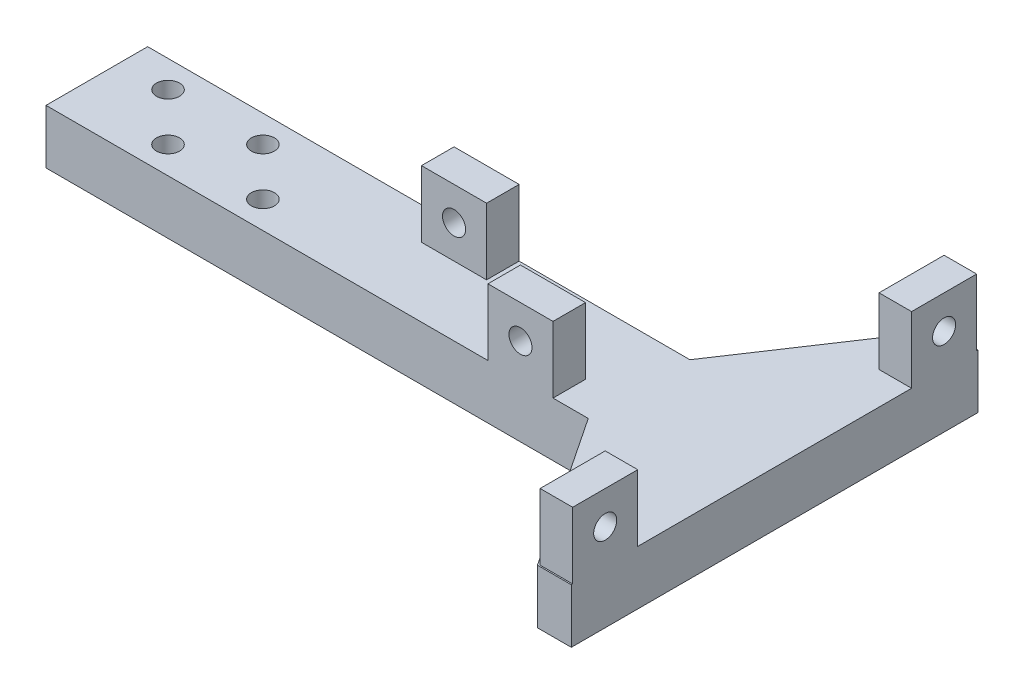
SolidWorks part; units mm, degrees
ref_plane "前视基准面" through (0, 0, 0) normal (0, 0, 1) x (1, 0, 0)
ref_plane "上视基准面" through (0, 0, 0) normal (0, 1, 0) x (1, 0, 0)
ref_plane "右视基准面" through (0, 0, 0) normal (1, 0, 0) x (0, 0, -1)
sketch "Sketch1" plane through (0, 0, 0) normal (0, 1, 0) x (1, 0, 0)
  line L0 (50, 30) -> (50, -30)
  line L1 (-50, 30) -> (50, 30) construction
  line L2 (-50, 30) -> (-50, -30) construction
  line L3 (-50, -30) -> (50, -30) construction
  line L4 (50, 30) -> (50, -30) construction
  line L5 (-50, 30) -> (50, -30) construction
  line L6 (-50, -30) -> (50, 30) construction
  line L7 (50, -30) -> (45, -30)
  line L8 (50, 30) -> (45, 30)
  line L9 (-50, 7.5) -> (-50, -7.5)
  line L10 (-50, 7.5) -> (30, 7.5)
  line L11 (30, 7.5) -> (30, -7.5) construction
  line L12 (30, -7.5) -> (-50, -7.5)
  line L13 (30, 7.5) -> (45, 30)
  line L14 (30, -7.5) -> (45, -30)
  point P0 (0, 0)
  point P5 (-50, 0)
  dimension "D1" = 15
  dimension "D2" = 20
  dimension "D3" = 5
  dimension "D4" = 60
  dimension "D5" = 100
extrude "Boss-Extrude1" add sketch "Sketch1" along normal blind 8
sketch "Sketch2" plane through (0, 8, 0) normal (0, 1, 0) x (1, 0, 0)
  line L0 (-50, 0) -> (50, 0) construction
  line L1 (50, 29.8) -> (45.2, 29.8)
  line L2 (50, 29.8) -> (50, 20.2)
  line L3 (50, 20.2) -> (45.2, 20.2)
  line L4 (45.2, 29.8) -> (45.2, 20.2)
  line L5 (-50, 7.5) -> (-50, -7.5) construction
  line L6 (50, -30) -> (50, 30) construction
  line L7 (45.2, -29.8) -> (45.2, -20.2)
  line L8 (50, -20.2) -> (45.2, -20.2)
  line L9 (50, -29.8) -> (50, -20.2)
  line L10 (50, -29.8) -> (45.2, -29.8)
  line L12 (24.8, -2.7) -> (15.2, -2.7)
  line L13 (24.8, -2.7) -> (24.8, -7.5)
  line L14 (24.8, -7.5) -> (15.2, -7.5)
  line L15 (15.2, -2.7) -> (15.2, -7.5)
  line L16 (-50, -7.5) -> (30, -7.5) construction
  line L17 (4.8, 2.7) -> (-4.8, 2.7)
  line L18 (4.8, 2.7) -> (4.8, 7.5)
  line L19 (4.8, 7.5) -> (-4.8, 7.5)
  line L20 (-4.8, 2.7) -> (-4.8, 7.5)
  line L21 (30, 7.5) -> (-50, 7.5) construction
  line L22 (50, 30) -> (45, 30) construction
  dimension "D1" = 9.6
  dimension "D2" = 4.8
  dimension "D3" = 25.2
  dimension "D4" = 9.6
  dimension "D5" = 4.8
  dimension "D6" = 10.4
  dimension "D7" = 0.2
extrude "Boss-Extrude2" add sketch "Sketch2" along normal blind 9.8
sketch "Sketch3" plane through (45.2, 0, 0) normal (-1, 0, 0) x (0, 0, 1)
  line L1 (-29.8, 17.8) -> (-20.2, 17.8) construction
  line L2 (-25, 17.8) -> (-25, 12.9) construction
  circle A0 centre (-25, 12.9) radius 1.7
  dimension "D1" = 4.9
  dimension "D2" = 3.4
extrude "Cut-Extrude1" cut sketch "Sketch3" against normal up to next
mirror "Mirror1" about plane through (0, 0, 0) normal (0, 0, 1) of "Cut-Extrude1"
sketch "Sketch4" plane through (0, 0, 2.7) normal (0, 0, -1) x (-1, 0, 0)
  line L1 (-24.8, 17.8) -> (-15.2, 17.8) construction
  line L2 (-20, 17.8) -> (-20, 12.9) construction
  circle A0 centre (-20, 12.9) radius 1.7
  dimension "D1" = 4.9
  dimension "D2" = 3.4
extrude "Cut-Extrude2" cut sketch "Sketch4" against normal up to next
sketch "Sketch5" plane through (0, 0, -2.7) normal (0, 0, 1) x (1, 0, 0)
  line L1 (-4.8, 17.8) -> (4.8, 17.8) construction
  line L2 (0, 17.8) -> (0, 12.9) construction
  circle A0 centre (0, 12.9) radius 1.7
  dimension "D1" = 4.9
  dimension "D2" = 3.4
extrude "Cut-Extrude3" cut sketch "Sketch5" against normal up to next
sketch "Sketch7" plane through (0, 8, 0) normal (0, 1, 0) x (1, 0, 0)
  line L0 (-50, 7.5) -> (-50, -7.5) construction
  line L3 (-4.8, 7.5) -> (-50, 7.5) construction
  line L4 (-46.5, 3.5) -> (-44.75, 0.4689)
  line L5 (-44.75, 0.4689) -> (-41.25, 0.4689)
  line L6 (-41.25, 0.4689) -> (-39.5, 3.5)
  line L7 (-39.5, 3.5) -> (-41.25, 6.5311)
  line L8 (-41.25, 6.5311) -> (-44.75, 6.5311)
  line L9 (-44.75, 6.5311) -> (-46.5, 3.5)
  line L11 (-32.5, -3.5) -> (-34.25, -0.4689)
  line L12 (-34.25, -0.4689) -> (-37.75, -0.4689)
  line L13 (-37.75, -0.4689) -> (-39.5, -3.5)
  line L14 (-39.5, -3.5) -> (-37.75, -6.5311)
  line L15 (-37.75, -6.5311) -> (-34.25, -6.5311)
  line L16 (-34.25, -6.5311) -> (-32.5, -3.5)
  circle A0 centre (-43, 3.5) radius 3.0311 construction
  circle A1 centre (-36, -3.5) radius 3.0311 construction
  dimension "D1" = 3.5
  dimension "D2" = 7
  dimension "D3" = 4
  dimension "D4" = 7
  dimension "D5" = 7
extrude "Cut-Extrude4" cut sketch "Sketch7" against normal up to surface (3 mm away) from offset 5 up to face at (18.75, 0, 0) offset against normal yes
sketch "Sketch10" plane through (0, 3, 0) normal (0, -1, 0) x (1, 0, 0)
  line L0 (-44.75, -0.4689) -> (-41.25, -6.5311) construction
  line L1 (-37.75, 6.5311) -> (-34.25, 0.4689) construction
  circle A0 centre (-43, -3.5) radius 1.7
  circle A1 centre (-36, 3.5) radius 1.7
  dimension "D1" = 3.4
extrude "Cut-Extrude7" cut sketch "Sketch10" against normal blind 5
pattern_linear "LPattern2" count 2 spacing 14 along (1, 0, 0) of "Cut-Extrude4", "Cut-Extrude7"
